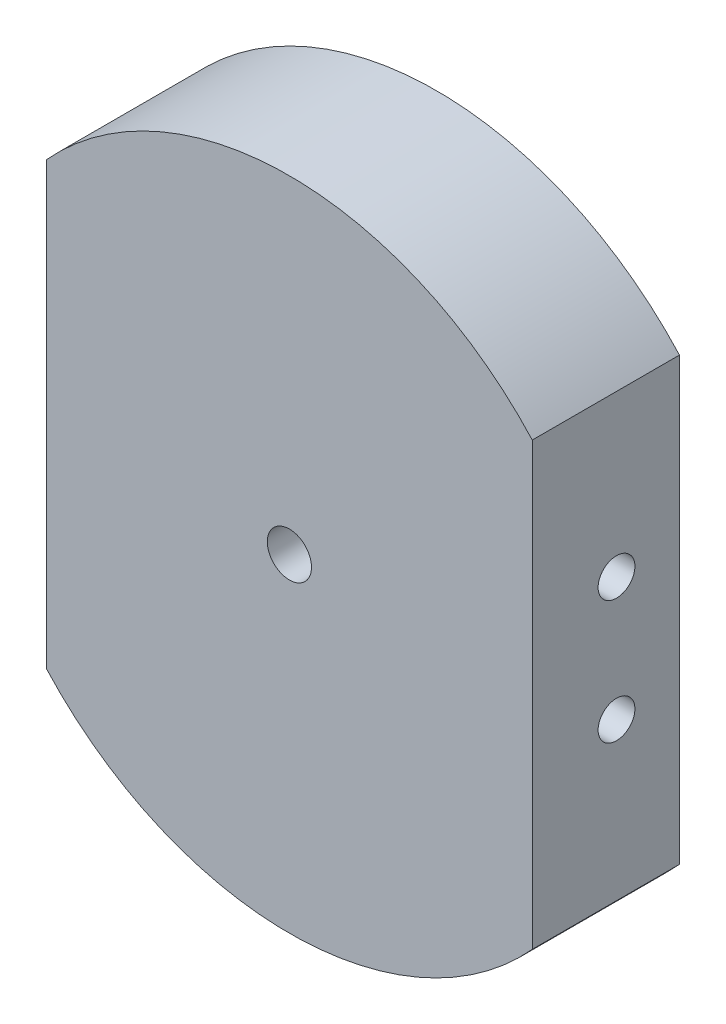
SolidWorks part; units mm, degrees
ref_plane "Front Plane" through (0, 0, 0) normal (0, 0, 1) x (1, 0, 0)
ref_plane "Top Plane" through (0, 0, 0) normal (0, 1, 0) x (1, 0, 0)
ref_plane "Right Plane" through (0, 0, 0) normal (1, 0, 0) x (0, 0, -1)
sketch "Sketch1" plane through (0, 0, 0) normal (0, 0, 1) x (1, 0, 0)
  circle A0 centre (0, 0) radius 55
  circle A1 centre (0, 0) radius 3
extrude "Boss-Extrude1" add sketch "Sketch1" along normal blind 20
sketch "Sketch2" plane through (0, 0, 20) normal (0, 0, 1) x (1, 0, 0)
  line L0 (-55, 0) -> (55, 0) construction
  line L1 (-54.0833, -10) -> (54.0833, -10) construction
  line L2 (-47.962, 14.4195) -> (-41.962, 14.4195) construction
  line L7 (-41.362, 16.6207) -> (-41.362, -16.6207)
  line L8 (0, 0) -> (0, 19.7694) construction
  line L9 (41.362, 16.6207) -> (41.362, -16.6207)
  line L11 (48.562, 0) -> (48.562, -1.9737)
  circle A0 centre (0, 0) radius 55 construction
  circle A1 centre (0, 0) radius 52
  arc A2 (-41.362, -16.6207) -> (41.362, -16.6207) centre (0, 0) ccw
  arc A7 (-41.362, 16.6207) -> (41.362, 16.6207) centre (0, 0) cw
  dimension "D3" = 10
extrude "Cut-Extrude1" cut sketch "Sketch2" against normal blind 10
sketch "Sketch3" plane through (0, 0, 20) normal (0, 0, 1) x (1, 0, 0)
  line L2 (-41.362, 16.6207) -> (-41.362, -16.6207)
  line L3 (41.362, -16.6207) -> (41.362, 16.6207)
  line L4 (-41.362, 16.6207) -> (-41.362, -16.6207)
  line L5 (41.362, -16.6207) -> (41.362, 16.6207)
  circle A0 centre (0, 0) radius 73.6451
  arc A2 (41.362, 16.6207) -> (-41.362, 16.6207) centre (0, 0) ccw
  arc A3 (-41.362, -16.6207) -> (41.362, -16.6207) centre (0, 0) ccw
  arc A4 (41.362, 16.6207) -> (-41.362, 16.6207) centre (0, 0) ccw
  arc A5 (-41.362, -16.6207) -> (41.362, -16.6207) centre (0, 0) ccw
  dimension "D1" = 0
extrude "Cut-Extrude2" cut sketch "Sketch3" against normal blind 40
sketch "Sketch6" plane through (0, 0, 0) normal (0, 0, -1) x (-1, 0, 0)
  line L0 (0, 44.5764) -> (0, -44.5764) construction
  line L1 (33, 29.9676) -> (59.4435, 26.8152)
  line L2 (-33, 29.9676) -> (33, 29.9676)
  line L3 (-33, 29.9676) -> (-33, -29.9676)
  line L4 (-33, -29.9676) -> (33, -29.9676)
  line L5 (33, 29.9676) -> (33, -29.9676)
  line L6 (-33, 29.9676) -> (33, -29.9676) construction
  line L7 (-33, -29.9676) -> (33, 29.9676) construction
  line L8 (59.4435, 26.8152) -> (59.4435, -14.2915)
  line L9 (59.4435, -14.2915) -> (33, -29.9676)
  line L10 (-33, 29.9676) -> (-58.6751, 18.0052)
  line L11 (-58.6751, 18.0052) -> (-58.6751, -19.3878)
  line L12 (-58.6751, -19.3878) -> (-33, -29.9676)
  arc A0 (41.362, 16.6207) -> (-41.362, 16.6207) centre (0, 0) ccw construction
  arc A1 (-41.362, -16.6207) -> (41.362, -16.6207) centre (0, 0) ccw construction
  point P8 (0, 0)
  arc M6 (41.362, 16.6207) -> (-41.362, 16.6207) centre (0, 0) ccw
  line M7 (-41.362, 16.6207) -> (-41.362, -16.6207)
  arc M8 (-41.362, -16.6207) -> (41.362, -16.6207) centre (0, 0) ccw
  line M9 (41.362, -16.6207) -> (41.362, 16.6207)
  dimension "D1" = 66
extrude "Cut-Extrude4" cut sketch "Sketch6" against normal blind 58 contours L11 L12 L10 M8 M7 M6 | L3 M6 M7 M8 | L9 L8 L1 M6 M9 M8 | L5 M6 M8 M9
sketch "Sketch5" plane through (33, 0, 0) normal (1, 0, 0) x (0, 0, -1)
  line L0 (-84.2797, -0.4989) -> (-24.2797, -0.4989) construction
  line L1 (-20, -29.9676) -> (-20, 29.9676) construction
  circle A0 centre (-8.5533, -8.6389) radius 2.5
  circle A1 centre (-8.5533, 8.14) radius 2.5
  dimension "D1" = 8.14
  dimension "D2" = 5
  dimension "D3" = 11.4467
extrude "Cut-Extrude3" cut sketch "Sketch5" against normal blind 110
